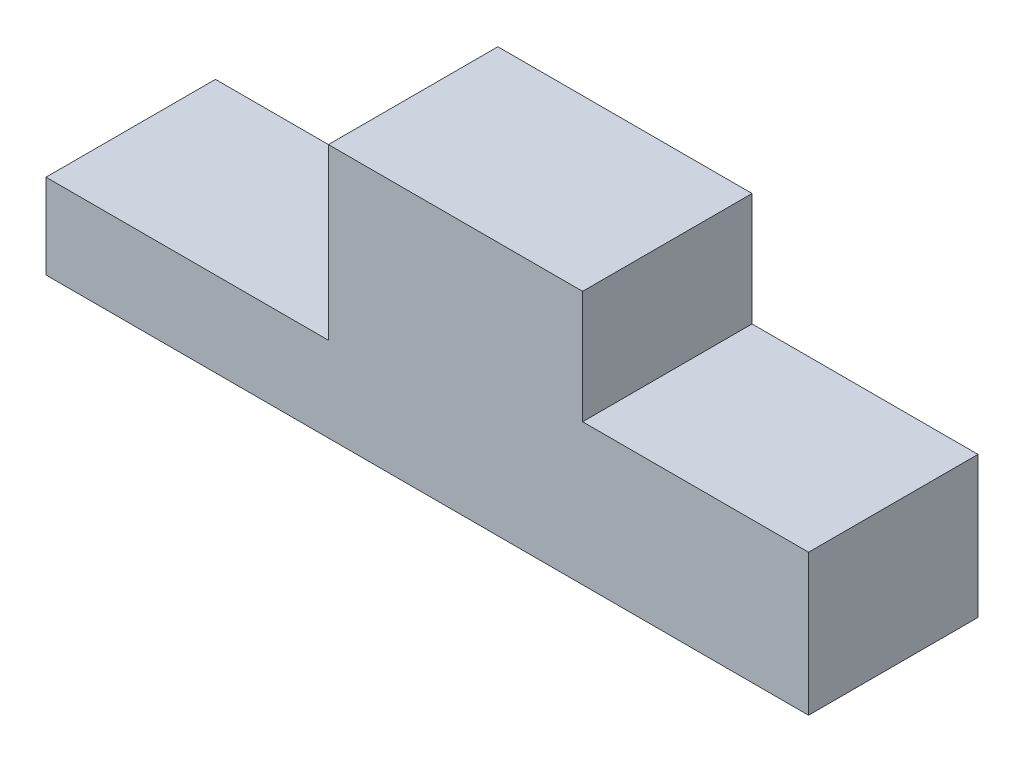
SolidWorks part; units mm, degrees
ref_plane "Piano frontale" through (0, 0, 0) normal (0, 0, 1) x (1, 0, 0)
ref_plane "Piano superiore" through (0, 0, 0) normal (0, 1, 0) x (1, 0, 0)
ref_plane "Piano destro" through (0, 0, 0) normal (1, 0, 0) x (0, 0, -1)
sketch "Schizzo1" plane through (0, 0, 0) normal (0, 1, 0) x (1, 0, 0)
  line L0 (0, -16.5) -> (0, 16.5) construction
  line L1 (-50, 15) -> (0, 15)
  line L2 (-50, 15) -> (-50, -15)
  line L3 (-50, -15) -> (0, -15)
  line L4 (0, 15) -> (0, -15)
  line L5 (-41.25, 0) -> (41.25, 0) construction
  dimension "D1" = 15
  dimension "D2" = 30
  dimension "D3" = 50
extrude "Estrusione-Estrusione1" add sketch "Schizzo1" along normal blind 15
sketch "Schizzo3" plane through (0, 0, 0) normal (0, 0, 1) x (1, 0, 0)
  line L1 (0, 0) -> (45, 0)
  line L2 (0, 0) -> (0, 15)
  line L3 (0, 15) -> (45, 15)
  line L4 (45, 0) -> (45, 15)
  dimension "D1" = 45
  dimension "D2" = 15
extrude "Estrusione-Estrusione2" add sketch "Schizzo3" along normal mid plane 30
sketch "Schizzo4" plane through (0, 0, 0) normal (0, 0, 1) x (1, 0, 0)
  line L1 (45, 15) -> (0, 15)
  line L2 (45, 15) -> (45, 45)
  line L3 (45, 45) -> (0, 45)
  line L4 (0, 15) -> (0, 45)
  dimension "D2" = 30
  dimension "D1" = 45
extrude "Estrusione-Estrusione3" add sketch "Schizzo4" along normal mid plane 30
sketch "Schizzo5" plane through (0, 0, 0) normal (0, 1, 0) x (1, 0, 0)
  line L1 (45, 15) -> (85, 15)
  line L2 (45, 15) -> (45, -15)
  line L3 (45, -15) -> (85, -15)
  line L4 (85, 15) -> (85, -15)
  dimension "D1" = 40
extrude "Estrusione-Estrusione4" add sketch "Schizzo5" along normal blind 25
equation "\"lunghezza_1\"=50"
equation "\"D3@Schizzo1\"=\"lunghezza_1\""
equation "\"lunghezza_2\"=30"
equation "\"D2@Schizzo4\"=\"lunghezza_2\""
equation "\"lunghezza_3\"=40"
equation "\"D1@Schizzo5\"=\"lunghezza_3\""
